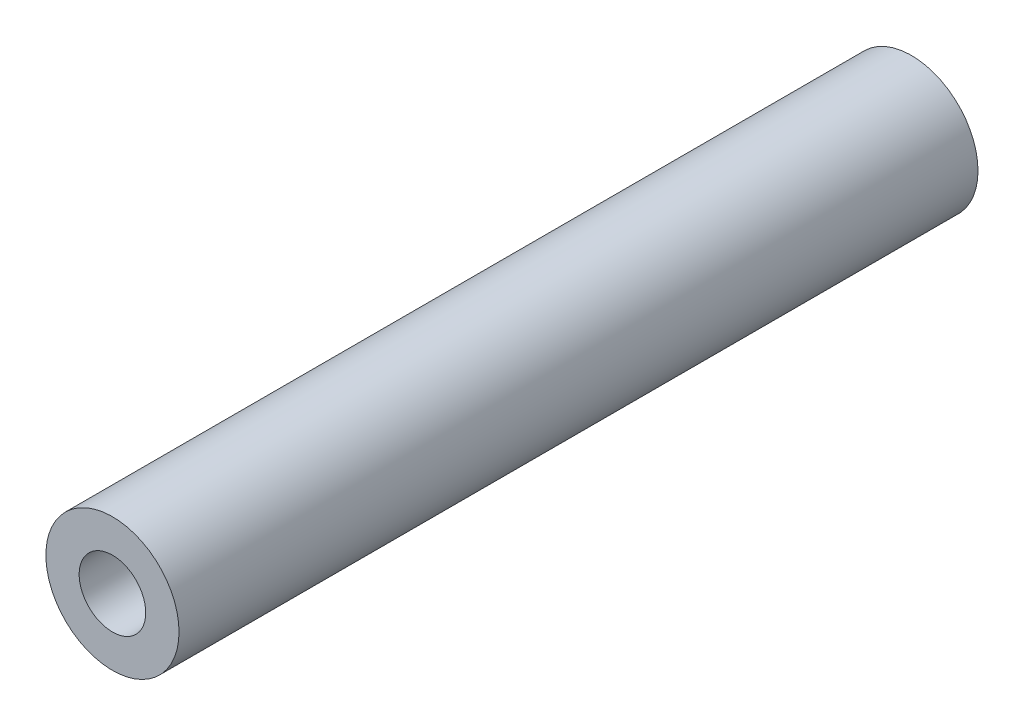
SolidWorks part; units mm, degrees
material "6061 Alloy"
ref_plane "Front Plane" through (0, 0, 0) normal (0, 0, 1) x (1, 0, 0)
ref_plane "Top Plane" through (0, 0, 0) normal (0, 1, 0) x (1, 0, 0)
ref_plane "Right Plane" through (0, 0, 0) normal (1, 0, 0) x (0, 0, -1)
sketch "Sketch1" plane through (0, 0, 0) normal (0, 0, 1) x (1, 0, 0)
  circle A0 centre (0, 0) radius 5
  circle A1 centre (0, 0) radius 2.5
  dimension "D1" = 5
  dimension "D2" = 10
extrude "Boss-Extrude1" add sketch "Sketch1" along normal blind 60
